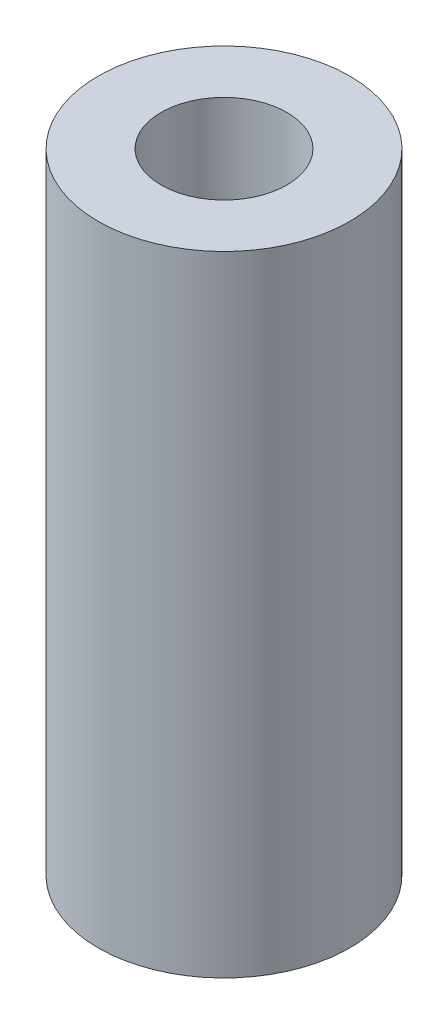
SolidWorks part; units mm, degrees
ref_plane "Front Plane" through (0, 0, 0) normal (0, 0, 1) x (1, 0, 0)
ref_plane "Top Plane" through (0, 0, 0) normal (0, 1, 0) x (1, 0, 0)
ref_plane "Right Plane" through (0, 0, 0) normal (1, 0, 0) x (0, 0, -1)
sketch "Sketch1" plane through (0, 0, 0) normal (0, 1, 0) x (1, 0, 0)
  circle A0 centre (0, 0) radius 50.8
  circle A1 centre (0, 0) radius 25.4
  dimension "D1" = 101.6
  dimension "D2" = 50.8
extrude "Boss-Extrude1" add sketch "Sketch1" along normal blind 254
equation "\"Body_Tube_OD\"= 4in"
equation "\"Body_Tube_ID\"= 2in"
equation "\"D1@Sketch1\"=\"Body_Tube_OD\""
equation "\"D2@Sketch1\"=\"Body_Tube_ID\""
equation "\"Aft_Section_Length\" = 10in"
equation "\"D1@Boss-Extrude1\"=\"Aft_Section_Length\""
